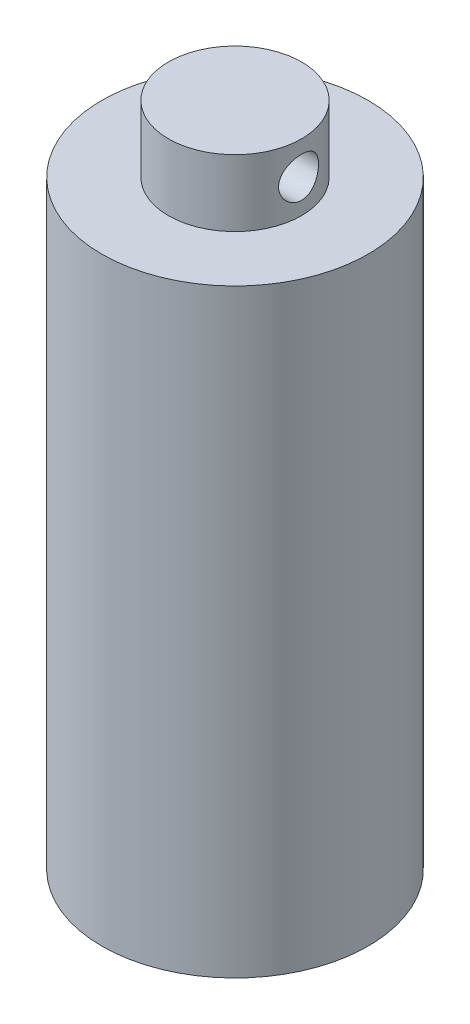
SolidWorks part; units mm, degrees
ref_plane "Front Plane" through (0, 0, 0) normal (0, 0, 1) x (1, 0, 0)
ref_plane "Top Plane" through (0, 0, 0) normal (0, 1, 0) x (1, 0, 0)
ref_plane "Right Plane" through (0, 0, 0) normal (1, 0, 0) x (0, 0, -1)
other "Configuration Table"
sketch "Sketch1" plane through (0, 0, 0) normal (0, 1, 0) x (1, 0, 0)
  circle A0 centre (0, 0) radius 2.54
  dimension "D1" = 5.08
extrude "Boss-Extrude1" add sketch "Sketch1" along normal blind 11.43
sketch "Sketch2" plane through (0, 11.43, 0) normal (0, 1, 0) x (1, 0, 0)
  circle A0 centre (0, 0) radius 1.27
  dimension "D1" = 2.54
extrude "Boss-Extrude2" add sketch "Sketch2" along normal blind 1.27
sketch "Sketch3" plane through (0, 0, 0) normal (1, 0, 0) x (0, 0, -1)
  line L0 (0, 12.7) -> (0, 11.43) construction
  line L1 (1.27, 12.7) -> (-1.27, 12.7) construction
  line L2 (2.54, 11.43) -> (-2.54, 11.43) construction
  circle A0 centre (0, 12.065) radius 0.381
  dimension "D1" = 0.762
extrude "Cut-Extrude1" cut sketch "Sketch3" against normal through all both and the other way through all
scale "Scale1" scale about centroid uniform scaling yes scale factor 1.5
